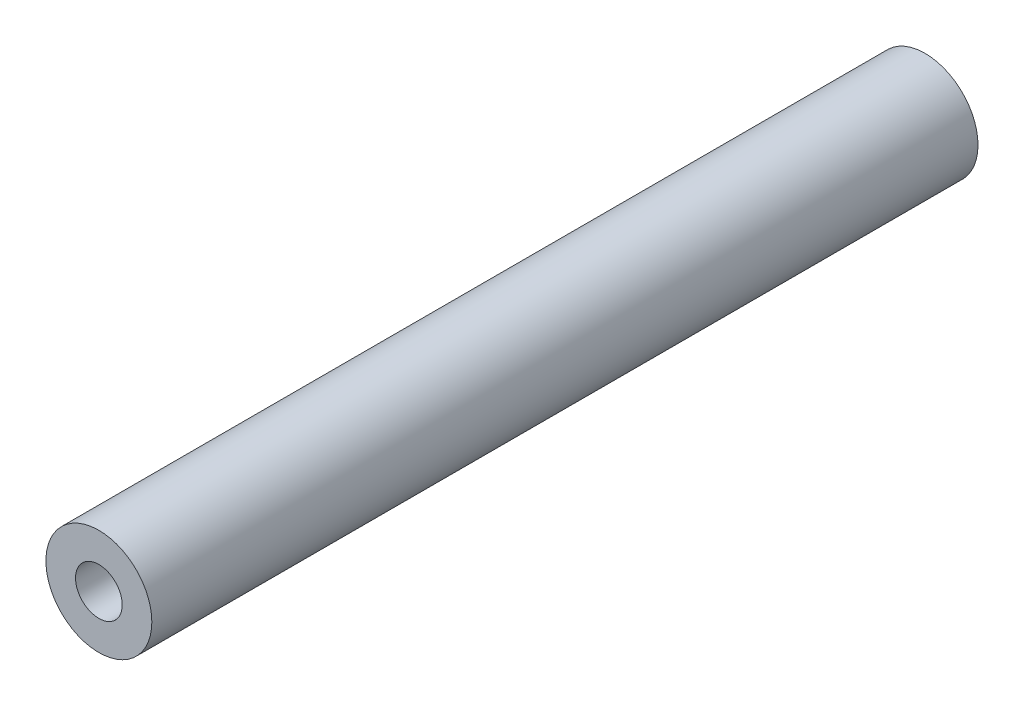
SolidWorks part; units mm, degrees
material "6061 Alloy"
ref_plane "Front Plane" through (0, 0, 0) normal (0, 0, 1) x (1, 0, 0)
ref_plane "Top Plane" through (0, 0, 0) normal (0, 1, 0) x (1, 0, 0)
ref_plane "Right Plane" through (0, 0, 0) normal (1, 0, 0) x (0, 0, -1)
sketch "Sketch1" plane through (0, 0, 0) normal (0, 0, 1) x (1, 0, 0)
  line L1 (-4.7625, 0) -> (4.7625, 0) construction
  dimension "OD" = 9.525
sketch "Sketch2" plane through (0, 0, 0) normal (1, 0, 0) x (0, 0, -1)
  line L0 (37.1475, 0) -> (-37.1475, 0)
  point P0 (-30.9563, 0)
  point P3 (30.9563, 0)
  point P4 (0, 0)
  dimension "Length" = 74.295
  dimension "D1" = 6.1913
  dimension "D2" = 6.1913
sketch "Sketch3" plane through (0, 0, 0) normal (0, 0, 1) x (1, 0, 0)
  circle A0 centre (0, 0) radius 4.7625
extrude "Boss-Extrude1" add sketch "Sketch3" along normal up to vertex (37.1475 mm away) and the other way up to vertex (37.1475 mm away) up to point (0, 0, 37.1475) other way up to point (0, 0, -37.1475)
sketch "Sketch4" plane through (0, 0, 37.1475) normal (0, 0, 1) x (1, 0, 0)
  circle A0 centre (0, 0) radius 2.5
  dimension "D1" = 5
hole_wizard "Tap Drill for M5x0.8 Tap1" positions "3DSketch2" profile "Sketch6" hole size "M5x0.8" standard "ANSI Metric"
sketch3d "3DSketch2"
  point P0 (0, 0, 37.1475)
  point P3 (0, 0, 37.1475)
sketch "Sketch6" plane through (0, 0, 37.1475) normal (1, 0, 0) x (0, -1, 0)
  line L0 (0, 0) -> (0, 13.9618)
  line L1 (0, 13.9618) -> (2.1, 12.7)
  line L2 (2.1, 12.7) -> (2.1, 0)
  line L5 (2.1, 0) -> (0, 0)
  line L10 (0, 13.9618) -> (-2.1, 12.7) construction
  line L11 (0, -6.35) -> (0, 107.95) construction
  dimension "Hole Dia." = 4.2
  dimension "Hole Depth" = 12.7
  dimension "Drill Angle" = 118
mirror "Mirror1" about plane through (0, 0, 0) normal (0, 0, 1) of "Tap Drill for M5x0.8 Tap1"
equation "\"D1@Sketch2\"=\"Length@Sketch2\"/12"
equation "\"D2@Sketch2\"=\"Length@Sketch2\"/12"
